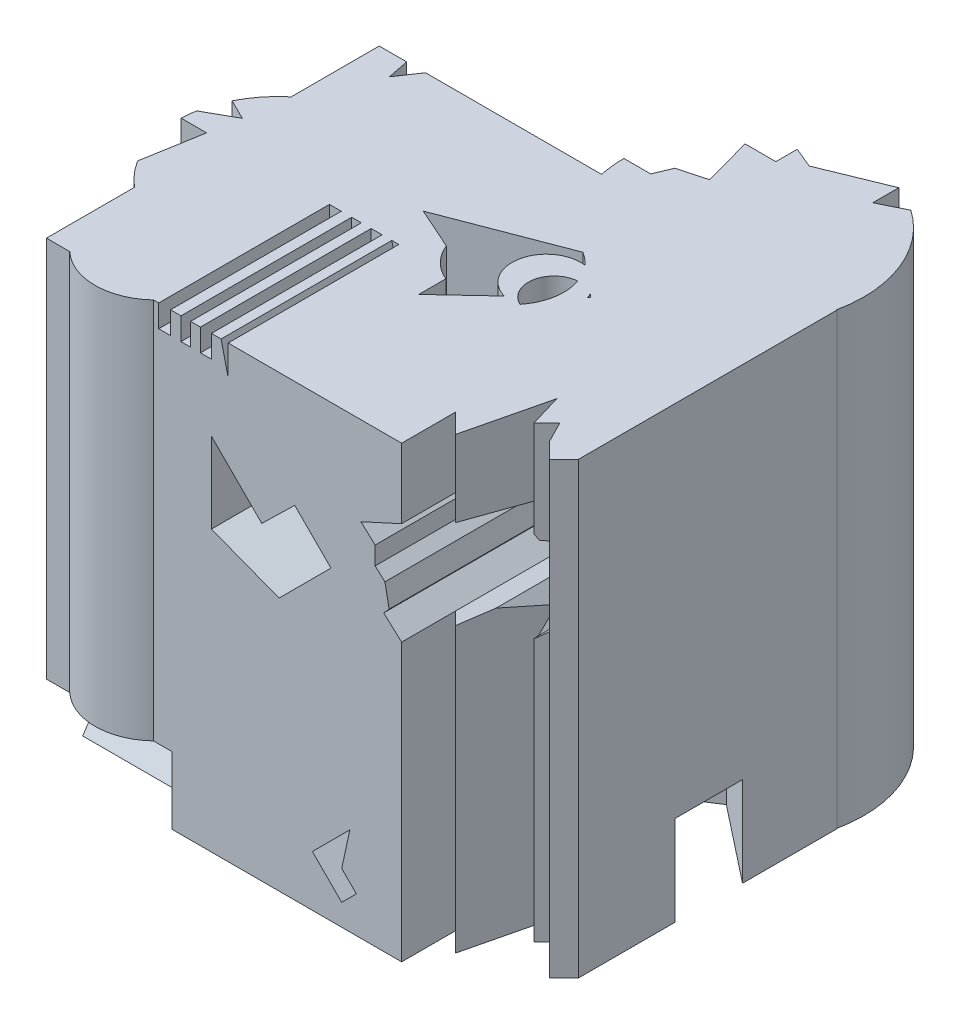
SolidWorks part; units mm, degrees
ref_plane "Front Plane" through (0, 0, 0) normal (0, 0, 1) x (1, 0, 0)
ref_plane "Top Plane" through (0, 0, 0) normal (0, 1, 0) x (1, 0, 0)
ref_plane "Right Plane" through (0, 0, 0) normal (1, 0, 0) x (0, 0, -1)
sketch "Sketch1" plane through (0, 0, 0) normal (0, 1, 0) x (1, 0, 0)
  line L0 (-46.6481, -23.5227) -> (-46.6481, -48.4122)
  line L1 (-46.6481, 45.6681) -> (16.2107, 45.6681)
  line L2 (-46.6481, 45.6681) -> (-46.6481, 20.7787)
  line L3 (-46.6481, -48.4122) -> (-40.0623, -48.4122)
  line L4 (82.7123, 45.6681) -> (82.7123, -48.4122)
  line L5 (-16.3859, -48.4122) -> (82.7123, -48.4122)
  line L6 (82.5736, 45.6681) -> (82.7123, 45.6681)
  arc A0 (82.5736, 45.6681) -> (16.2107, 45.6681) centre (49.3922, 52.7242) ccw
  arc A1 (-46.6481, 20.7787) -> (-46.6481, -23.5227) centre (-28.2241, -1.372) ccw
  arc A2 (-40.0623, -48.4122) -> (-16.3859, -48.4122) centre (-28.2241, -35.8681) ccw
extrude "Boss-Extrude1" add sketch "Sketch1" along normal blind 127
sketch "Sketch2" plane through (0, 127, 0) normal (0, 1, 0) x (1, 0, 0)
  line L0 (53.7713, -48.4122) -> (53.7713, -33.1331)
  line L1 (-16.3859, -48.4122) -> (82.7123, -48.4122) construction
  line L2 (53.7713, -33.1331) -> (59.2453, -38.6071)
  line L3 (59.2453, -38.6071) -> (64.8057, -15.566)
  line L4 (64.8057, -15.566) -> (67.5604, -24.818)
  line L5 (67.5604, -24.818) -> (71.2109, -21.1675)
  line L6 (71.2109, -21.1675) -> (74.2401, -27.0866)
  line L7 (74.2401, -27.0866) -> (78.6103, -31.4568)
  line L8 (78.6103, -31.4568) -> (82.7123, -27.3549)
  line L9 (82.7123, -48.4122) -> (82.7123, 45.6681) construction
  line L10 (82.7123, -27.3549) -> (82.7123, -48.4122)
  line L11 (82.7123, -48.4122) -> (53.7713, -48.4122)
extrude "Cut-Extrude1" cut sketch "Sketch2" against normal blind 127
sketch "Sketch3" plane through (0, 127, 0) normal (0, 1, 0) x (1, 0, 0)
  line L0 (-54.0213, 11.4578) -> (-48.2902, 8.6075)
  line L1 (-48.2902, 8.6075) -> (-56.5294, 4.0045)
  line L2 (-54.0213, 11.4578) -> (-59.5733, 8.6075)
  line L3 (-59.5733, 8.6075) -> (-56.5294, 4.0045)
  arc A0 (-46.6481, 20.7787) -> (-46.6481, -23.5227) centre (-28.2241, -1.372) ccw construction
extrude "Cut-Extrude2" cut sketch "Sketch3" against normal blind 127
sketch "Sketch4" plane through (0, 127, 0) normal (0, 1, 0) x (1, 0, 0)
  line L0 (68.7119, 80.6086) -> (61.4994, 77.0622)
  line L1 (61.4994, 77.0622) -> (61.4994, 84.4135)
  line L2 (61.4994, 84.4135) -> (43.5067, 77.0622)
  line L3 (43.5067, 77.0622) -> (37.7321, 79.4869)
  line L4 (37.7321, 79.4869) -> (37.7321, 73.422)
  line L5 (37.7321, 73.422) -> (29.0192, 73.422)
  line L6 (29.0192, 73.422) -> (32.7958, 59.6417)
  line L7 (32.7958, 59.6417) -> (25.0527, 57.5197)
  line L8 (25.0527, 57.5197) -> (23.0391, 52.7242)
  line L9 (23.0391, 52.7242) -> (15.4688, 52.7242)
  line L10 (15.4688, 52.7242) -> (7.7037, 71.7296)
  line L11 (7.7037, 71.7296) -> (36.6075, 93.9485)
  line L12 (36.6075, 93.9485) -> (52.503, 98.3048)
  line L13 (52.503, 98.3048) -> (65.1056, 93.0132)
  line L14 (65.1056, 93.0132) -> (69.999, 86.6476)
  line L15 (69.999, 86.6476) -> (68.7119, 80.6086)
  arc A0 (82.5736, 45.6681) -> (16.2107, 45.6681) centre (49.3922, 52.7242) ccw construction
extrude "Cut-Extrude3" cut sketch "Sketch4" against normal blind 127
sketch "Sketch5" plane through (0, 0, 48.4122) normal (0, 0, 1) x (1, 0, 0)
  line L0 (23.5517, 96.6758) -> (33.7949, 86.4325)
  line L1 (33.7949, 86.4325) -> (19.1196, 71.7572)
  line L2 (19.1196, 71.7572) -> (0, 79.0949)
  line L3 (0, 79.0949) -> (0, 101.8287)
  line L4 (0, 101.8287) -> (14.231, 87.5977)
  line L5 (14.231, 87.5977) -> (23.5517, 96.6758)
extrude "Cut-Extrude4" cut sketch "Sketch5" against normal blind 127
sketch "Sketch6" plane through (-46.6481, 0, 0) normal (-1, 0, 0) x (0, 0, 1)
  line L0 (38.182, 0) -> (33.4007, 7.0243)
  line L1 (23.5227, 0) -> (48.4122, 0) construction
  line L2 (33.4007, 7.0243) -> (37.2174, 9.6223)
  line L3 (37.2174, 9.6223) -> (35.3091, 16.7838)
  line L4 (35.3091, 16.7838) -> (38.182, 16.7838)
  line L5 (38.182, 16.7838) -> (40.6057, 14.3602)
  line L6 (40.6057, 14.3602) -> (44.8429, 18.5974)
  line L7 (44.8429, 18.5974) -> (44.8429, 22.5919)
  line L8 (44.8429, 22.5919) -> (48.4122, 19.0226)
  line L9 (48.4122, 127) -> (48.4122, 0) construction
  line L11 (48.4122, 0) -> (38.182, 0)
  line L12 (48.4122, 0) -> (59.0126, 0)
  line L13 (59.0126, 0) -> (59.0126, 19.0226)
  line L14 (59.0126, 19.0226) -> (48.4122, 19.0226)
extrude "Cut-Extrude5" cut sketch "Sketch6" against normal blind 35.56
sketch "Sketch7" plane through (0, 0, 48.4122) normal (0, 0, 1) x (1, 0, 0)
  line L0 (39.1324, 25.0165) -> (28.5268, 14.411)
  line L1 (28.5268, 14.411) -> (36.8276, 6.1102)
  line L2 (36.8276, 6.1102) -> (40.9779, 10.2606)
  line L3 (40.9779, 10.2606) -> (36.8276, 14.411)
  line L4 (36.8276, 14.411) -> (39.1324, 25.0165)
extrude "Cut-Extrude6" cut sketch "Sketch7" against normal blind 45.72
sketch "Sketch8" plane through (0, 127, 0) normal (0, 1, 0) x (1, 0, 0)
  line L0 (-57.0028, 0) -> (-49.7853, 0)
  line L1 (-49.7853, 0) -> (-52.6666, -16.6252)
  line L2 (-62.2965, -13.8297) -> (-57.0028, 0)
  arc A0 (-56.5294, 4.0045) -> (-46.6481, -23.5227) centre (-28.2241, -1.372) ccw construction
  arc A1 (-52.6666, -16.6252) -> (-62.2965, -13.8297) centre (-44.9323, 28.0009) cw
extrude "Cut-Extrude7" cut sketch "Sketch8" against normal blind 25.4
sketch "Sketch9" plane through (0, 0, 0) normal (0, -1, 0) x (1, 0, 0)
  line L0 (82.7123, 0) -> (39.6074, -9.1566)
  line L1 (82.7123, 27.3549) -> (82.7123, -45.6681) construction
  line L2 (39.6074, -9.1566) -> (54.7938, -19.0214)
  line L3 (54.7938, -19.0214) -> (48.9283, -28.051)
  line L4 (48.9283, -28.051) -> (61.1598, -35.9965)
  line L5 (61.1598, -35.9965) -> (82.7123, -19.0214)
  line L6 (82.7123, -19.0214) -> (82.7123, 0)
extrude "Cut-Extrude8" cut sketch "Sketch9" against normal blind 25.4
sketch "Sketch10" plane through (0, 0, 48.4122) normal (0, 0, 1) x (1, 0, 0)
  line L0 (53.7713, 107.2912) -> (42.2562, 102.0172)
  line L1 (53.7713, 0) -> (53.7713, 127) construction
  line L2 (42.2562, 102.0172) -> (46.2872, 98.3368)
  line L3 (46.2872, 98.3368) -> (46.2872, 93.2162)
  line L4 (46.2872, 93.2162) -> (49.0454, 90.6979)
  line L5 (49.0454, 90.6979) -> (50.2353, 84.5961)
  line L6 (50.2353, 84.5961) -> (48.7032, 82.918)
  line L7 (48.7032, 82.918) -> (53.7713, 78.2909)
  line L9 (53.7713, 107.2912) -> (66.0506, 103.0306)
  line L10 (66.0506, 103.0306) -> (68.3262, 98.3368)
  line L11 (68.3262, 98.3368) -> (77.0432, 97.21)
  line L12 (77.0432, 97.21) -> (72.6847, 93.8493)
  line L13 (72.6847, 93.8493) -> (76.0454, 89.4908)
  line L14 (76.0454, 89.4908) -> (69.6974, 84.5961)
  line L15 (69.6974, 84.5961) -> (77.0432, 83.6465)
  line L16 (77.0432, 83.6465) -> (72.8714, 78.2909)
  line L17 (72.8714, 78.2909) -> (67.0141, 73.7745)
  line L18 (67.0141, 73.7745) -> (61.4669, 80.9687)
  line L19 (61.4669, 80.9687) -> (53.7713, 78.2909)
extrude "Cut-Extrude9" cut sketch "Sketch10" against normal blind 48.26
fillet "Fillet2" radius 12.7 1 edges at (-15.2187, 0, -45.6681)
sketch "Sketch11" plane through (0, 127, 0) normal (0, 1, 0) x (1, 0, 0)
  line L0 (-33.5611, 45.6681) -> (-37.667, 39.5458)
  line L1 (16.2107, 45.6681) -> (-46.6481, 45.6681) construction
  line L2 (-37.667, 39.5458) -> (-38.874, 45.6681)
  line L3 (-38.874, 45.6681) -> (-33.5611, 45.6681)
extrude "Cut-Extrude10" cut sketch "Sketch11" against normal blind 48.26
sketch "Sketch12" plane through (0, 127, 0) normal (0, 1, 0) x (1, 0, 0)
  line L0 (32.6226, 23.954) -> (0, 11.4712)
  line L1 (0, 11.4712) -> (11.7851, 6.2091)
  line L2 (19.7689, -1.9229) -> (19.7689, -9.559)
  line L3 (19.7689, -9.559) -> (32.2525, 2.1201)
  line L5 (44.3112, 13.4017) -> (44.8595, 13.9147)
  arc A0 (11.7851, 6.2091) -> (19.7689, -1.9229) centre (25.2784, 11.4712) ccw
  arc A1 (36.1171, 21.0775) -> (32.6226, 23.954) centre (25.2784, 11.4712) ccw
  arc A2 (44.8595, 13.9147) -> (43.935, 14.7474) centre (39.5378, 8.9359) ccw
  arc A3 (36.4979, 2.3125) -> (38.9673, 16.2011) centre (25.2784, 11.4712) ccw
  arc A4 (44.3112, 13.4017) -> (43.935, 14.7474) centre (34.8106, 11.4712) ccw
  arc A5 (36.1171, 21.0775) -> (32.2525, 2.1201) centre (34.8106, 11.4712) ccw
  arc A6 (38.9673, 16.2011) -> (36.4979, 2.3125) centre (39.5378, 8.9359) ccw
extrude "Cut-Extrude11" cut sketch "Sketch12" against normal blind 48.26
sketch "Sketch13" plane through (0, 0, 48.4122) normal (0, 0, 1) x (1, 0, 0)
  line L0 (-14.9079, 127) -> (-14.9079, 120.6788)
  line L1 (-16.3859, 127) -> (53.7713, 127) construction
  line L2 (-14.9079, 120.6788) -> (-11.5555, 120.6788)
  line L3 (-11.5555, 120.6788) -> (-11.5555, 127)
  line L4 (-11.5555, 127) -> (-14.9079, 127)
  line L5 (-8.6148, 127) -> (-8.6148, 120.6788)
  line L6 (-8.6148, 120.6788) -> (-5.8885, 120.6788)
  line L7 (-5.8885, 120.6788) -> (-5.8885, 127)
  line L8 (-5.8885, 127) -> (-8.6148, 127)
  line L9 (-3.1043, 127) -> (0, 127)
  line L10 (0, 127) -> (0, 120.6788)
  line L11 (0, 120.6788) -> (-3.1043, 120.6788)
  line L12 (-3.1043, 120.6788) -> (-3.1043, 127)
  line L13 (2.7323, 127) -> (4.7148, 127)
  line L14 (4.7148, 127) -> (4.7148, 118.5746)
  line L15 (4.7148, 118.5746) -> (2.7323, 127)
extrude "Cut-Extrude12" cut sketch "Sketch13" against normal blind 48.26
